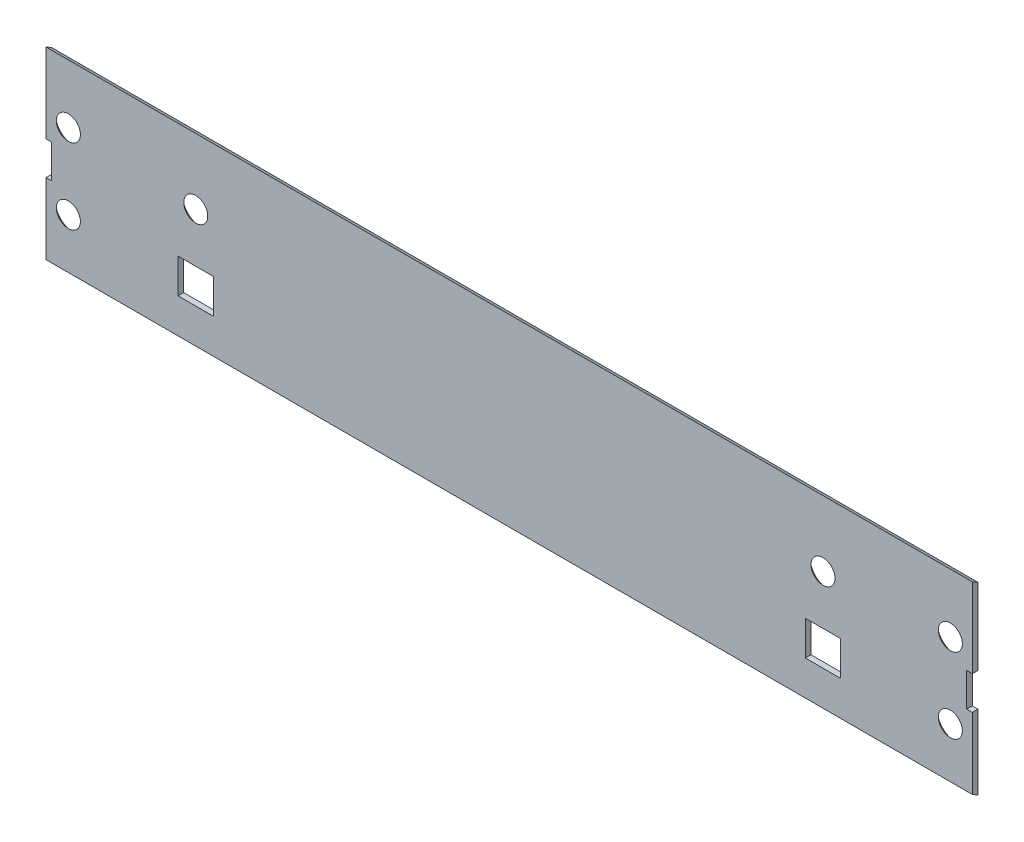
SolidWorks part; units mm, degrees
material "1023 Carbon Steel Sheet (SS)"
ref_plane "Front Plane" through (0, 0, 0) normal (0, 0, 1) x (1, 0, 0)
ref_plane "Top Plane" through (0, 0, 0) normal (0, 1, 0) x (1, 0, 0)
ref_plane "Right Plane" through (0, 0, 0) normal (1, 0, 0) x (0, 0, -1)
sketch "Sketch1" plane through (0, 0, 0) normal (0, 0, 1) x (1, 0, 0)
  line L1 (-87.757, 17.7546) -> (87.757, 17.7546)
  line L2 (-87.757, 17.7546) -> (-87.757, -17.7546)
  line L3 (-87.757, -17.7546) -> (87.757, -17.7546)
  line L4 (87.757, 17.7546) -> (87.757, -17.7546)
  line L5 (-87.757, 17.7546) -> (87.757, -17.7546) construction
  line L6 (-87.757, -17.7546) -> (87.757, 17.7546) construction
  point P0 (0, 0)
  dimension "D1" = 175.514
  dimension "D2" = 35.5092
extrude "Boss-Extrude1" add sketch "Sketch1" along normal blind 1.0668
sketch "Sketch7" plane through (-87.757, 0, 0) normal (-1, 0, 0) x (0, 0, 1)
  line L0 (0, 17.1387) -> (1.0668, 17.7546)
  line L1 (0, 17.7546) -> (0, -17.7546) construction
  line L2 (1.0668, 17.7546) -> (0, 17.7546)
  line L3 (0, 17.7546) -> (0, 17.1387)
  line L4 (1.0668, 17.7546) -> (1.0668, -17.7546) construction
  line L5 (0, -17.7546) -> (1.0668, -17.1387)
  line L6 (1.0668, -17.1387) -> (1.0668, -17.7546)
  line L7 (1.0668, -17.7546) -> (0, -17.7546)
  dimension "D1" = 60
  dimension "D2" = 60
extrude "Cut-Extrude2" cut sketch "Sketch7" against normal through all
sketch "Sketch8" plane through (0, 0, 0) normal (0, 0, -1) x (-1, 0, 0)
  line L4 (56.0324, -4.0396) -> (56.0324, -10.5674)
  line L5 (56.0324, -10.5674) -> (62.738, -10.5674)
  line L6 (62.738, -10.5674) -> (62.738, -4.0396)
  line L7 (62.738, -4.0396) -> (56.0324, -4.0396)
  line L10 (0, 17.1387) -> (0, -17.7546) construction
  line L11 (-87.757, 17.1387) -> (87.757, 17.1387) construction
  line L16 (87.757, -17.7546) -> (-87.757, -17.7546) construction
  line L17 (-87.757, 2.6803) -> (-87.757, -3.6697)
  line L18 (-87.757, -3.6697) -> (-86.6902, -3.6697)
  line L19 (-86.6902, -3.6697) -> (-86.6902, 2.6803)
  line L20 (56.2102, -4.2174) -> (56.2102, -10.3896)
  line L21 (56.2102, -10.3896) -> (62.5602, -10.3896)
  line L22 (62.5602, -10.3896) -> (62.5602, -4.2174)
  line L23 (62.5602, -4.2174) -> (56.2102, -4.2174)
  line L24 (-86.6902, 2.6803) -> (-87.757, 2.6803)
  line L25 (56.2102, -4.2174) -> (56.2102, -10.3896) construction
  line L26 (56.2102, -10.3896) -> (62.5602, -10.3896) construction
  line L27 (62.5602, -10.3896) -> (62.5602, -4.2174) construction
  line L28 (62.5602, -4.2174) -> (56.2102, -4.2174) construction
  line L29 (-62.6301, -4.2174) -> (-62.6301, -10.3896)
  line L30 (-62.6301, -10.3896) -> (-56.2801, -10.3896)
  line L31 (-56.2801, -10.3896) -> (-56.2801, -4.2174)
  line L32 (-56.2801, -4.2174) -> (-62.6301, -4.2174)
  line L33 (-62.6301, -4.2174) -> (-62.6301, -10.3896) construction
  line L34 (-62.6301, -10.3896) -> (-56.2801, -10.3896) construction
  line L35 (-56.2801, -10.3896) -> (-56.2801, -4.2174) construction
  line L38 (-56.2801, -4.2174) -> (-62.6301, -4.2174) construction
  line L39 (-62.8079, -4.0396) -> (-62.8079, -10.5674)
  line L40 (-62.8079, -10.5674) -> (-56.1023, -10.5674)
  line L41 (-56.1023, -10.5674) -> (-56.1023, -4.0396)
  line L43 (-56.1023, -4.0396) -> (-62.8079, -4.0396)
  line L52 (86.76, -3.6697) -> (87.8268, -3.6697)
  line L57 (87.8268, -3.6697) -> (87.8268, 2.6803)
  line L58 (87.8268, 2.6803) -> (86.76, 2.6803)
  line L59 (86.76, 2.6803) -> (86.76, -3.6697)
  line L60 (86.76, -3.6697) -> (87.8268, -3.6697)
  line L61 (87.8268, -3.6697) -> (87.8268, 2.6803)
  line L62 (87.8268, 2.6803) -> (86.76, 2.6803)
  line L63 (86.76, 2.6803) -> (86.76, -3.6697)
  line L64 (-87.757, 2.6803) -> (-87.757, -3.6697)
  line L65 (-87.757, -3.6697) -> (-86.6902, -3.6697)
  line L66 (-86.6902, -3.6697) -> (-86.6902, 2.6803)
  line L67 (-86.6902, 2.6803) -> (-87.757, 2.6803)
  dimension "D2" = 0
  dimension "D7" = 0
  dimension "D1" = 0
  dimension "D3" = 0.1778
  dimension "D6" = 0
extrude "Cut-Extrude3" cut sketch "Sketch8" against normal through all
hole_wizard "CSK for #6 Flat Head Machine Screw (100)1" positions "Sketch10" profile "Sketch9" countersink size "#6" standard "ANSI Inch" end condition through all
sketch "Sketch10" plane through (0, 0, 0) normal (0, 0, -1) x (-1, 0, 0)
  point P0 (-59.4551, 5.3076)
  point P3 (-83.585, 6.6432)
  point P6 (-83.585, -7.6443)
  point P9 (59.3852, 5.3076)
  point P12 (83.5152, 6.6432)
  point P17 (83.5152, -7.6443)
sketch "Sketch9" plane through (59.4551, 5.3076, 0) normal (1, 0, 0) x (0, 1, 0)
  line L0 (0, 0) -> (0, 1.0668)
  line L1 (0, 1.0668) -> (1.8986, 1.0668)
  line L2 (1.8986, 1.0668) -> (1.8986, 1.38)
  line L3 (1.8986, 1.38) -> (3.5433, 0)
  line L5 (3.5433, 0) -> (0, 0)
  line L6 (-1.8987, 1.38) -> (-3.5433, 0) construction
  line L11 (0, -6.35) -> (0, 107.95) construction
  dimension "Thru Hole Dia." = 3.7973
  dimension "Thru Hole Depth" = 1.0668
  dimension "Near C'Sink Dia." = 7.0866
  dimension "Near C'Sink Angle" = 100
